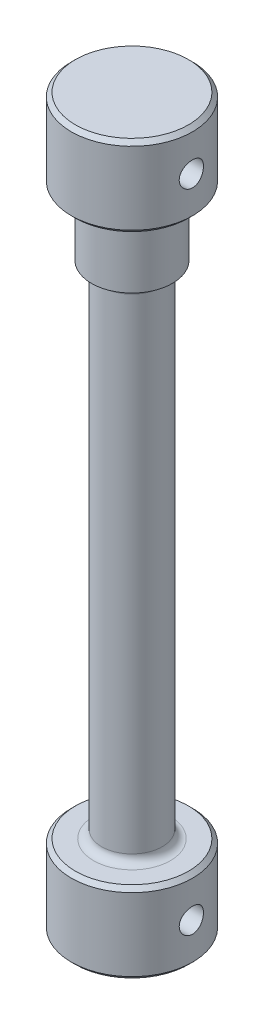
SolidWorks part; units mm, degrees
ref_plane "Plan1" through (0, 0, 0) normal (0, 0, 1) x (1, 0, 0)
ref_plane "Plan2" through (0, 0, 0) normal (0, 1, 0) x (1, 0, 0)
ref_plane "Plan3" through (0, 0, 0) normal (1, 0, 0) x (0, 0, -1)
sketch "Esquisse1" plane through (0, 0, 0) normal (0, 0, 1) x (1, 0, 0)
  line L0 (0, 0) -> (0, -74) construction
  line L1 (0, 0) -> (-14, 0)
  line L2 (-14, 0) -> (-15, -1)
  line L3 (-15, -1) -> (-15, -19)
  line L4 (-15, -19) -> (-14, -20)
  line L5 (-14, -20) -> (-12, -20)
  line L6 (-10, -22) -> (-10, -36)
  line L7 (-10, -36) -> (-9.5, -36)
  line L8 (-7.5, -38) -> (-7.5, -158)
  line L9 (0, -180) -> (-14, -180)
  line L10 (-14, -160) -> (-9.5, -160)
  line L11 (-15, -161) -> (-14, -160)
  line L12 (-15, -179) -> (-15, -161)
  line L13 (-14, -180) -> (-15, -179)
  line L14 (0, -180) -> (0, 0)
  line L15 (0, -90) -> (21.7367, -90) construction
  arc A0 (-10, -22) -> (-12, -20) centre (-12, -22) ccw
  arc A1 (-7.5, -38) -> (-9.5, -36) centre (-9.5, -38) ccw
  arc A2 (-7.5, -158) -> (-9.5, -160) centre (-9.5, -158) cw
  dimension "D7" = 2
  dimension "D11" = 2
  dimension "D1" = 15
  dimension "D2" = 45
  dimension "D3" = 18
  dimension "D4" = 1
  dimension "D5" = 45
  dimension "D6" = 1
  dimension "D8" = 10
  dimension "D9" = 7.5
  dimension "D10" = 16
  dimension "D12" = 180
revolve "Base-Révolution" add sketch "Esquisse1" angle 360 about L0
sketch "Esquisse2" plane through (0, 0, 0) normal (1, 0, 0) x (0, 0, -1)
  line L0 (0, 0) -> (0, -74) construction
  line L1 (14, 0) -> (-14, 0) construction
  line L2 (-14, -180) -> (14, -180) construction
  circle A0 centre (0, -10) radius 3
  circle A1 centre (0, -170) radius 3
  dimension "D2" = 6
  dimension "D3" = 6
  dimension "D1" = 160
  dimension "D4" = 10
  dimension "D5" = 10
extrude "Enlèv. mat.-Extru.1" cut sketch "Esquisse2" against normal mid plane 50
sketch "Esquisse4" plane through (0, 0, 0) normal (1, 0, 0) x (0, 0, -1)
  point P0 (0, -170)
